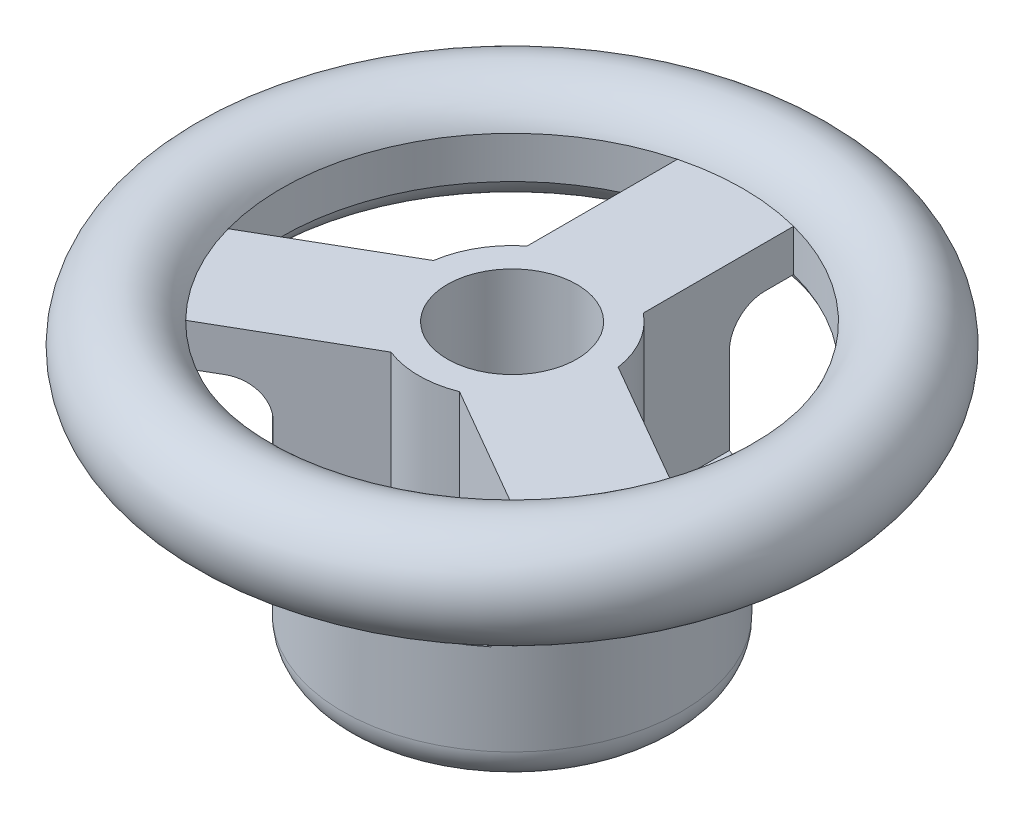
SolidWorks part; units mm, degrees
ref_plane "Front Plane" through (0, 0, 0) normal (0, 0, 1) x (1, 0, 0)
ref_plane "Top Plane" through (0, 0, 0) normal (0, 1, 0) x (1, 0, 0)
ref_plane "Right Plane" through (0, 0, 0) normal (1, 0, 0) x (0, 0, -1)
sketch "Sketch1" plane through (0, 0, 0) normal (0, 0, 1) x (1, 0, 0)
  line L0 (0, 0) -> (0, 1.7031) construction
  line L1 (0, 0) -> (7.89, 0) construction
  line L2 (0, 0.5) -> (5.5257, 0.5)
  line L3 (4.86, -0.5) -> (5.5257, -0.5)
  line L4 (4.06, -1.3) -> (4.06, -5.55)
  line L5 (3.26, -6.35) -> (0, -6.35)
  line L6 (0, -6.35) -> (0, 0)
  line L7 (0, 0.5) -> (0, 0)
  arc A1 (5.5257, -0.5) -> (5.5257, 0.5) centre (6.655, 0) ccw
  arc A2 (4.06, -5.55) -> (3.26, -6.35) centre (3.26, -5.55) cw
  arc A3 (4.06, -1.3) -> (4.86, -0.5) centre (4.86, -1.3) cw
  dimension "D1" = 1.235
  dimension "D2" = 1
  dimension "D3" = 7.89
  dimension "D5" = 0.8
  dimension "D4" = 6.35
  dimension "D6" = 3.26
revolve "Revolve1" add sketch "Sketch1" angle 360 about L0
sketch "Sketch2" plane through (0, 0.5, 0) normal (0, 1, 0) x (1, 0, 0)
  circle A0 centre (0, 0) radius 1.55
  dimension "D1" = 3.1
extrude "Cut-Extrude5" cut sketch "Sketch2" against normal blind 14.87
sketch "Sketch3" plane through (0, 0.5, 0) normal (0, 1, 0) x (1, 0, 0)
  line L0 (1.39, 1.7502) -> (-1.39, 1.7502) construction
  line L5 (-1.39, 1.7502) -> (-1.39, 5.3481)
  line L7 (1.39, 1.7502) -> (1.39, 5.3481)
  line L8 (2.2107, 0.3287) -> (5.3266, -1.4703)
  line L9 (0.8207, -2.0789) -> (3.9366, -3.8778)
  line L10 (-0.8207, -2.0789) -> (-3.9366, -3.8778)
  line L11 (-2.2107, 0.3287) -> (-5.3266, -1.4703)
  circle A3 centre (0, 0) radius 2.235
  circle A4 centre (0, 0) radius 5.5257
  circle A5 centre (0, 0) radius 5.5257 construction
  point P10 (0, 1.7502)
  point P22 (0, 0)
  point P23 (0, 0)
  circle M3 centre (0, 0) radius 5.5257
  dimension "D1" = 4.47
  dimension "D2" = 2.78
  dimension "D3" = 3
extrude "Cut-Extrude10" cut sketch "Sketch3" against normal blind 3.88 contours A3 L5 L11 M3 | A3 L8 L7 M3 | A3 L10 L9 M3
sketch "Sketch5" plane through (0, -6.35, 0) normal (0, -1, 0) x (1, 0, 0)
  circle A0 centre (0, 0) radius 3.26
  circle A1 centre (0, 0) radius 3.26 construction
extrude "Cut-Extrude11" cut sketch "Sketch5" against normal blind 2.18
